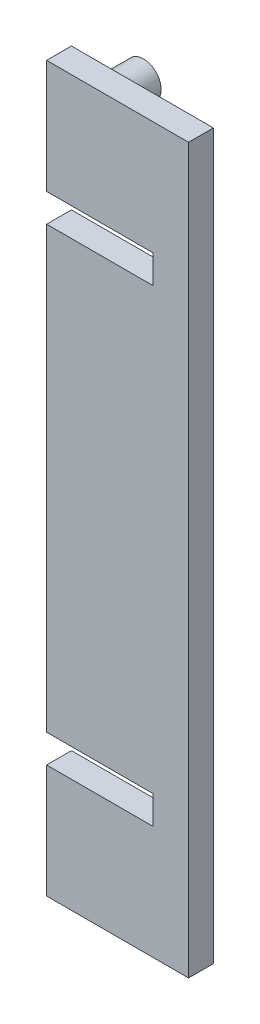
SolidWorks part; units mm, degrees
ref_plane "前视基准面" through (0, 0, 0) normal (0, 0, 1) x (1, 0, 0)
ref_plane "上视基准面" through (0, 0, 0) normal (0, 1, 0) x (1, 0, 0)
ref_plane "右视基准面" through (0, 0, 0) normal (1, 0, 0) x (0, 0, -1)
other "Configuration Table"
sketch "草图1" plane through (0, 0, 0) normal (0, 0, 1) x (1, 0, 0)
  line L0 (-11.815, -22.8257) -> (3.185, -22.8257)
  line L1 (-11.815, 39.1743) -> (3.185, 39.1743)
  line L2 (-11.815, 39.1743) -> (-11.815, -22.8257)
  line L3 (-11.815, -22.8257) -> (3.185, -22.8257)
  line L4 (68.185, 39.1743) -> (68.185, -22.8257)
  line L5 (-11.815, 39.1743) -> (3.185, 39.1743)
  line L7 (3.185, -22.8257) -> (3.185, -42.8257)
  line L8 (3.185, -42.8257) -> (68.185, -42.8257)
  line L9 (68.185, -22.8257) -> (68.185, -42.8257)
  line L12 (3.185, 39.1743) -> (3.185, 59.1743)
  line L13 (3.185, 59.1743) -> (68.185, 59.1743)
  line L14 (68.185, 39.1743) -> (68.185, 59.1743)
  dimension "D1" = 62
  dimension "D2" = 80
  dimension "D3" = 20
  dimension "D4" = 65
  dimension "D5" = 20
  dimension "D6" = 65
extrude "凸台-拉伸1" add sketch "草图1" along normal blind 3.5 contours L4 L14 L13 L12 L1 L2 L0 L7 L8 L9
sketch "草图2" plane through (0, 0, 3.5) normal (0, 0, 1) x (1, 0, 0)
  line L1 (68.185, 59.1743) -> (8.185, 59.1743)
  line L2 (68.185, 59.1743) -> (68.185, -42.8257)
  line L3 (68.185, -42.8257) -> (8.185, -42.8257)
  line L4 (8.185, 59.1743) -> (8.185, -42.8257)
  line L5 (3.185, -42.8257) -> (68.185, -42.8257) construction
  dimension "D1" = 102
  dimension "D2" = 60
extrude "切除-拉伸1" cut sketch "草图2" against normal blind 3.5
sketch "草图7" plane through (3.185, 0, 0) normal (-1, 0, 0) x (0, 0, 1)
  line L1 (0, 59.1743) -> (3.5, 59.1743)
  line L2 (0, 59.1743) -> (0, 43.1743)
  line L3 (0, 43.1743) -> (3.5, 43.1743)
  line L4 (3.5, 59.1743) -> (3.5, 43.1743)
  line L5 (3.5, 39.1743) -> (3.5, 59.1743) construction
  line L7 (0, -42.8257) -> (3.5, -42.8257)
  line L8 (0, -42.8257) -> (0, -26.8257)
  line L9 (0, -26.8257) -> (3.5, -26.8257)
  line L10 (3.5, -42.8257) -> (3.5, -26.8257)
  line L11 (3.5, -22.8257) -> (3.5, -42.8257) construction
  dimension "D1" = 16
  dimension "D2" = 3.5
  dimension "D3" = 16
  dimension "D4" = 3.5
extrude "凸台-拉伸3" add sketch "草图7" along normal blind 15
sketch "草图6" plane through (0, 0, 0) normal (0, 0, -1) x (-1, 0, 0)
  circle A8 centre (6.6681, -38.8257) radius 1.25
  circle A9 centre (6.6681, -38.8257) radius 2.5
  circle A10 centre (6.6681, 1.1743) radius 1.25
  circle A11 centre (6.6681, 1.1743) radius 2.5
  circle A12 centre (6.6681, 15.1743) radius 1.25
  circle A13 centre (6.6681, 15.1743) radius 2.5
  circle A14 centre (6.6681, 55.1743) radius 1.25
  circle A15 centre (6.6681, 55.1743) radius 2.5
extrude "凸台-拉伸2" add sketch "草图6" along normal blind 5
